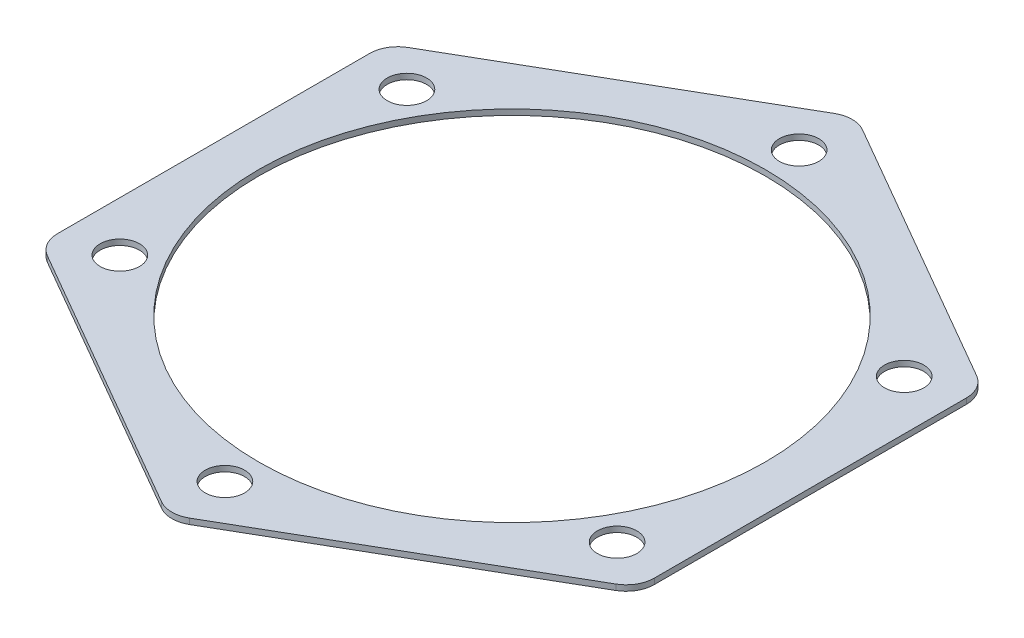
SolidWorks part; units mm, degrees
ref_plane "Front Plane" through (0, 0, 0) normal (0, 0, 1) x (1, 0, 0)
ref_plane "Top Plane" through (0, 0, 0) normal (0, 1, 0) x (1, 0, 0)
ref_plane "Right Plane" through (0, 0, 0) normal (1, 0, 0) x (0, 0, -1)
sketch "Sketch1" plane through (0, 0, 0) normal (0, 1, 0) x (1, 0, 0)
  line L1 (2.5, -59.7558) -> (50.5, -32.0429)
  line L2 (53, -27.7128) -> (53, 27.7128)
  line L3 (50.5, 32.0429) -> (2.5, 59.7558)
  line L4 (-2.5, 59.7558) -> (-50.5, 32.0429)
  line L5 (-53, 27.7128) -> (-53, -27.7128)
  line L6 (-50.5, -32.0429) -> (-2.5, -59.7558)
  circle A0 centre (0, 0) radius 53 construction
  circle A1 centre (0, 0) radius 51 construction
  circle A2 centre (0, 0) radius 45
  circle A3 centre (0, 51) radius 3.5
  circle A4 centre (44.1673, 25.5) radius 3.5
  circle A5 centre (44.1673, -25.5) radius 3.5
  circle A6 centre (0, -51) radius 3.5
  circle A7 centre (-44.1673, -25.5) radius 3.5
  circle A8 centre (-44.1673, 25.5) radius 3.5
  arc A9 (-50.5, 32.0429) -> (-53, 27.7128) centre (-48, 27.7128) ccw
  arc A10 (-53, -27.7128) -> (-50.5, -32.0429) centre (-48, -27.7128) ccw
  arc A11 (2.5, -59.7558) -> (-2.5, -59.7558) centre (0, -55.4256) cw
  arc A12 (50.5, -32.0429) -> (53, -27.7128) centre (48, -27.7128) ccw
  arc A13 (53, 27.7128) -> (50.5, 32.0429) centre (48, 27.7128) ccw
  arc A14 (2.5, 59.7558) -> (-2.5, 59.7558) centre (0, 55.4256) ccw
  point P25 (0, 0)
  point P30 (0, -61.1991)
  dimension "D2" = 102
  dimension "D3" = 90
  dimension "D4" = 7
  dimension "D6" = 5
  dimension "D1" = 106
  dimension "D5" = 6
extrude "Boss-Extrude1" add sketch "Sketch1" along normal blind 1
